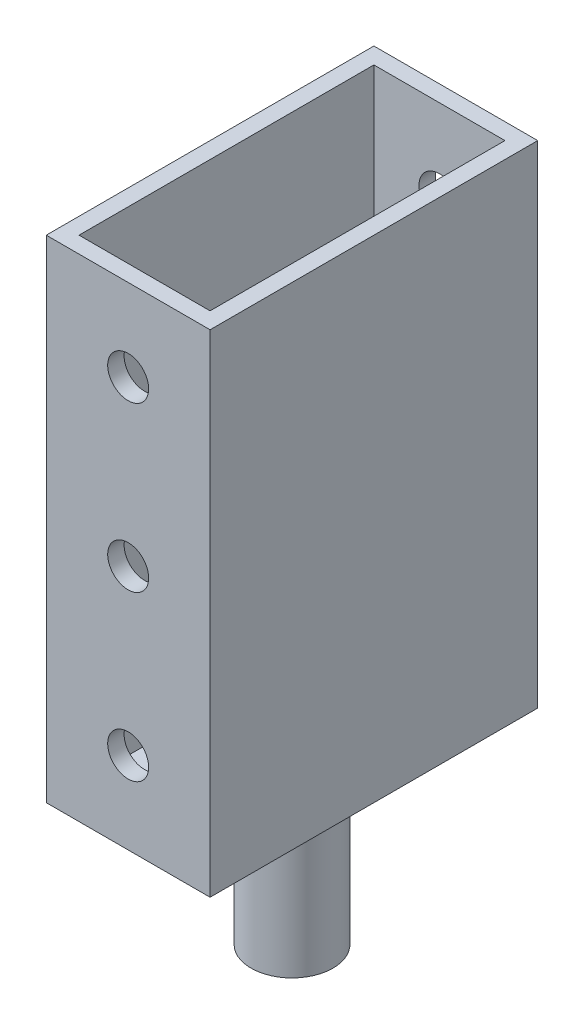
SolidWorks part; units mm, degrees
ref_plane "Front Plane" through (0, 0, 0) normal (0, 0, 1) x (1, 0, 0)
ref_plane "Top Plane" through (0, 0, 0) normal (0, 1, 0) x (1, 0, 0)
ref_plane "Right Plane" through (0, 0, 0) normal (1, 0, 0) x (0, 0, -1)
sketch "Sketch1" plane through (0, 0, 0) normal (0, 0, 1) x (1, 0, 0)
  line L1 (0, 0) -> (25.4, 0)
  line L2 (0, 0) -> (0, 76.2)
  line L3 (0, 76.2) -> (25.4, 76.2)
  line L4 (25.4, 0) -> (25.4, 76.2)
  dimension "D1" = 76.2
  dimension "D2" = 25.4
extrude "Boss-Extrude1" add sketch "Sketch1" along normal mid plane 50.8
sketch "Sketch2" plane through (0, 0, 25.4) normal (0, 0, 1) x (1, 0, 0)
  line L0 (0, 0) -> (25.4, 0) construction
  circle A1 centre (12.7, 38.1) radius 3.175
  circle A2 centre (12.7, 63.5) radius 3.175
  circle A3 centre (12.7, 88.9) radius 3.175
  circle A4 centre (12.7, 12.7) radius 3.175
  dimension "D1" = 25.4
  dimension "D2" = 6.35
  dimension "D3" = 6.35
  dimension "D4" = 6.35
  dimension "D5" = 12.7
  dimension "D7" = 25.4
  dimension "D8" = 25.4
extrude "Cut-Extrude1" cut sketch "Sketch2" against normal through all
sketch "Sketch3" plane through (0, 76.2, 0) normal (0, 1, 0) x (1, 0, 0)
  line L0 (0, -25.4) -> (0, 25.4) construction
  line L1 (2.54, -22.86) -> (22.86, -22.86)
  line L2 (2.54, -22.86) -> (2.54, 22.86)
  line L3 (2.54, 22.86) -> (22.86, 22.86)
  line L4 (22.86, -22.86) -> (22.86, 22.86)
  line L5 (25.4, -25.4) -> (0, -25.4) construction
  dimension "D1" = 20.32
  dimension "D2" = 45.72
  dimension "D3" = 2.54
  dimension "D4" = 2.54
extrude "Cut-Extrude2" cut sketch "Sketch3" against normal blind 73.66
sketch "Sketch4" plane through (0, 0, 0) normal (0, -1, 0) x (1, 0, 0)
  line L0 (0, 25.4) -> (25.4, 25.4) construction
  line L1 (0, 25.4) -> (0, -25.4) construction
  circle A0 centre (12.7, 0) radius 6.35
  dimension "D1" = 25.4
  dimension "D2" = 12.7
extrude "Boss-Extrude2" add sketch "Sketch4" along normal blind 25.4
